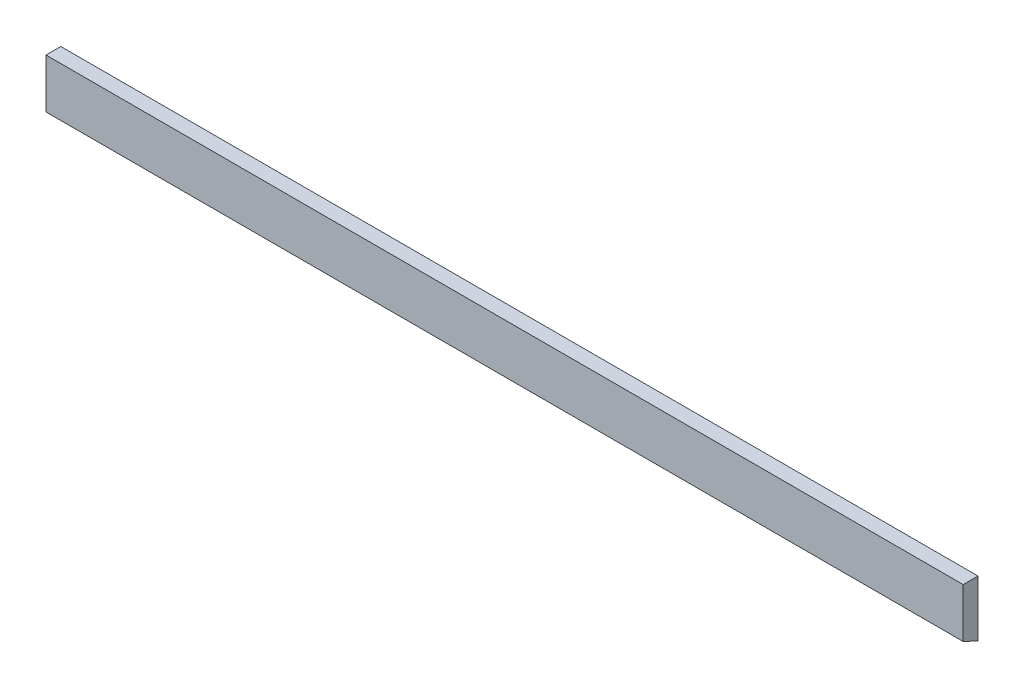
SolidWorks part; units mm, degrees
ref_plane "Front Plane" through (0, 0, 0) normal (0, 0, 1) x (1, 0, 0)
ref_plane "Top Plane" through (0, 0, 0) normal (0, 1, 0) x (1, 0, 0)
ref_plane "Right Plane" through (0, 0, 0) normal (1, 0, 0) x (0, 0, -1)
sketch "Esquisse1" plane through (0, 0, 0) normal (0, 0, 1) x (1, 0, 0)
  line L1 (0, 0) -> (-186, 0)
  line L2 (0, 0) -> (0, 10)
  line L3 (0, 10) -> (-186, 10)
  line L4 (-186, 0) -> (-186, 10)
  dimension "D1" = 186
  dimension "D2" = 10
extrude "Boss.-Extru.1" add sketch "Esquisse1" along normal blind 3
sketch "Esquisse2" plane through (0, 0, 0) normal (1, 0, 0) x (0, 0, -1)
  line L0 (0, 0) -> (0, -1.3989)
  line L1 (-3, 0) -> (61.3352, -30) construction
  line L2 (0, -1.3989) -> (-3, 0)
sketch "Esquisse3" plane through (0, 0, 0) normal (1, 0, 0) x (0, 0, -1)
  line L0 (-3, 0) -> (0, -1.3989)
  line L1 (0, -1.3989) -> (0, 0)
  line L2 (-3, 0) -> (0, 0)
extrude "Boss.-Extru.2" add sketch "Esquisse3" against normal up to surface (186 mm away) up to face at (-186, 5, 1.5)
